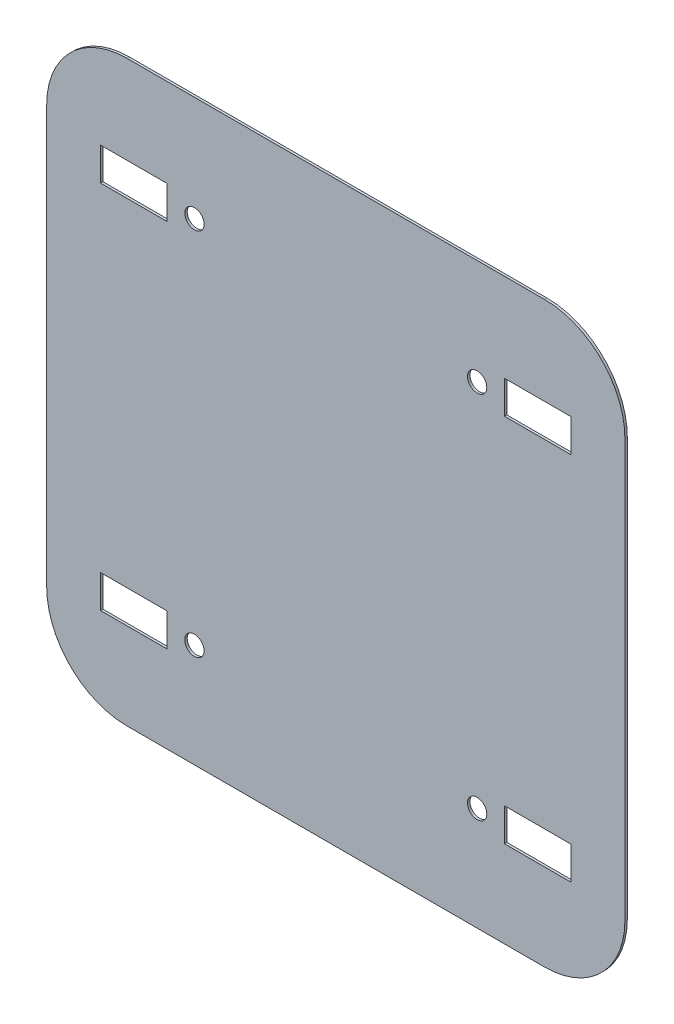
SolidWorks part; units mm, degrees
ref_plane "Front Plane" through (0, 0, 0) normal (0, 0, 1) x (1, 0, 0)
ref_plane "Top Plane" through (0, 0, 0) normal (0, 1, 0) x (1, 0, 0)
ref_plane "Right Plane" through (0, 0, 0) normal (1, 0, 0) x (0, 0, -1)
sketch "Sketch1" plane through (0, 0, 0) normal (0, 0, 1) x (1, 0, 0)
  line L5 (50, 0) -> (310, 0)
  line L6 (0, 50) -> (0, 310)
  line L7 (50, 360) -> (310, 360)
  line L8 (360, 50) -> (360, 310)
  arc A0 (0, 50) -> (50, 0) centre (50, 50) ccw
  arc A1 (360, 50) -> (310, 0) centre (310, 50) cw
  arc A2 (310, 360) -> (360, 310) centre (310, 310) cw
  arc A3 (50, 360) -> (0, 310) centre (50, 310) ccw
  point P7 (0, 0)
  point P13 (360, 360)
  point P16 (0, 360)
  dimension "D3" = 50
  dimension "D1" = 360
  dimension "D2" = 360
extrude "Boss-Extrude1" add sketch "Sketch1" along normal blind 1.5
sketch "Sketch2" plane through (0, 0, 1.5) normal (0, 0, 1) x (1, 0, 0)
  line L0 (0, 310) -> (0, 50) construction
  line L1 (33.5, 305) -> (75, 305)
  line L2 (33.5, 305) -> (33.5, 284.5)
  line L3 (33.5, 284.5) -> (75, 284.5)
  line L4 (75, 305) -> (75, 284.5)
  line L5 (310, 360) -> (50, 360) construction
  line L6 (285, 305) -> (285, 284.5)
  line L7 (285, 305) -> (326.5, 305)
  line L8 (326.5, 305) -> (326.5, 284.5)
  line L9 (285, 284.5) -> (326.5, 284.5)
  line L10 (285, 74.5) -> (285, 54)
  line L11 (285, 74.5) -> (326.5, 74.5)
  line L12 (326.5, 74.5) -> (326.5, 54)
  line L13 (285, 54) -> (326.5, 54)
  line L14 (33.5, 74.5) -> (33.5, 54)
  line L15 (33.5, 74.5) -> (75, 74.5)
  line L16 (75, 74.5) -> (75, 54)
  line L17 (33.5, 54) -> (75, 54)
  dimension "D1" = 41.5
  dimension "D2" = 20.5
  dimension "D3" = 75
  dimension "D4" = 55
  dimension "D7" = 210
  dimension "D8" = 210
  dimension "D9" = 210
  dimension "D10" = 41.5
  dimension "D5" = 2
  dimension "D6" = 2
extrude "Cut-Extrude1" cut sketch "Sketch2" against normal blind 1.5
hole_wizard "Ø12.0mm Dowel Hole1" positions "3DSketch1" profile "Sketch3" hole size "Ø12.0" standard "ISO" end condition through all
sketch3d "3DSketch1"
  line L0 (75, 284.5, 1.5) -> (75, 305, 1.5) construction
  line L1 (33.5, 284.5, 1.5) -> (75, 284.5, 1.5) construction
  line L2 (285, 305, 1.5) -> (285, 284.5, 1.5) construction
  line L3 (75, 74.5, 1.5) -> (33.5, 74.5, 1.5) construction
  point P0 (92, 294.5, 1.5)
  point P2 (268, 294.5, 1.5)
  point P4 (268, 64.5, 1.5)
  point P6 (92, 64.5, 1.5)
  dimension "D1" = 17
  dimension "D2" = 10
  dimension "D3" = 17
  dimension "D4" = 10
sketch "Sketch3" plane through (92, 294.5, 1.5) normal (1, 0, 0) x (0, -1, 0)
  line L0 (0, 0) -> (0, 1.5)
  line L1 (0, 1.5) -> (6, 1.5)
  line L2 (6, 1.5) -> (6, 0)
  line L5 (6, 0) -> (0, 0)
  line L11 (0, -6.35) -> (0, 107.95) construction
  dimension "Thru Hole Dia." = 12
  dimension "Thru Hole Depth" = 1.5
